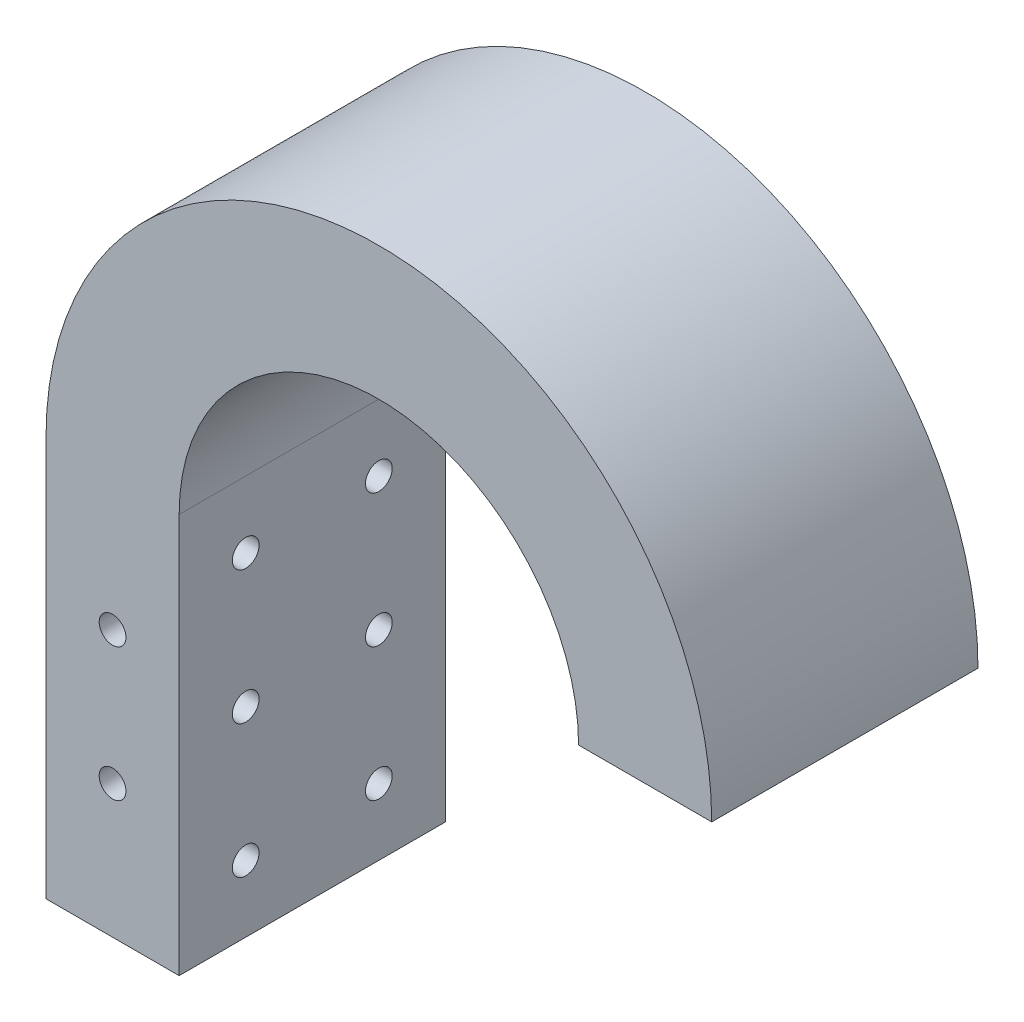
SolidWorks part; units mm, degrees
material "ABS"
ref_plane "Front" through (0, 0, 0) normal (0, 0, 1) x (1, 0, 0)
ref_plane "Top" through (0, 0, 0) normal (0, 1, 0) x (1, 0, 0)
ref_plane "Right" through (0, 0, 0) normal (1, 0, 0) x (0, 0, -1)
sketch "Sketch1" plane through (0, 0, 0) normal (0, 0, 1) x (1, 0, 0)
  line L0 (101.6, 76.2) -> (127, 76.2)
  line L1 (0, 0) -> (25.4, 0)
  line L2 (0, 0) -> (0, 76.2)
  line L4 (25.4, 0) -> (25.4, 76.2)
  arc A0 (25.4, 76.2) -> (101.6, 76.2) centre (63.5, 76.2) cw
  arc A1 (0, 76.2) -> (127, 76.2) centre (63.5, 76.2) cw
  dimension "D1" = 76.2
  dimension "D2" = 38.1
  dimension "D3" = 25.4
extrude "Boss-Extrude1" add sketch "Sketch1" along normal blind 50.8
hole_wizard "#10 Clearance Hole1" positions "Sketch2" profile "Sketch3" hole size "#10" standard "ANSI Inch"
sketch "Sketch2" plane through (0, 0, 50.8) normal (0, 0, 1) x (1, 0, 0)
  line L0 (0, 0) -> (25.4, 0) construction
  line L1 (0, 76.2) -> (0, 0) construction
  point P0 (12.7, 50.8)
  point P2 (12.7, 25.4)
  dimension "D1" = 25.4
  dimension "D2" = 25.4
  dimension "D3" = 12.7
sketch "Sketch3" plane through (12.7, 50.8, 50.8) normal (1, 0, 0) x (0, -1, 0)
  line L0 (0, 0) -> (0, 52.3328)
  line L1 (0, 52.3328) -> (2.5527, 50.799)
  line L2 (2.5527, 50.799) -> (2.5527, 0)
  line L5 (2.5527, 0) -> (0, 0)
  line L10 (0, 52.3328) -> (-2.5527, 50.799) construction
  line L11 (0, -6.35) -> (0, 107.95) construction
  dimension "Hole Dia." = 5.1054
  dimension "Hole Depth" = 50.799
  dimension "Drill Angle" = 118
hole_wizard "#10 Clearance Hole2" positions "Sketch4" profile "Sketch5" hole size "#10" standard "ANSI Inch"
sketch "Sketch4" plane through (0, 0, 0) normal (-1, 0, 0) x (0, 0, 1)
  line L0 (0, 76.2) -> (0, 0) construction
  line L1 (50.8, 0) -> (0, 0) construction
  point P0 (12.7, 38.1)
  point P2 (12.7, 12.7)
  point P4 (12.7, 63.5)
  point P12 (38.1, 63.5)
  point P14 (38.1, 12.7)
  point P16 (38.1, 38.1)
  dimension "D1" = 12.7
  dimension "D2" = 25.4
  dimension "D3" = 25.4
  dimension "D4" = 12.7
  dimension "D5" = 25.4
sketch "Sketch5" plane through (0, 38.1, 12.7) normal (0, 1, 0) x (0, 0, 1)
  line L0 (0, 0) -> (0, 26.9328)
  line L1 (0, 26.9328) -> (2.5527, 25.399)
  line L2 (2.5527, 25.399) -> (2.5527, 0)
  line L5 (2.5527, 0) -> (0, 0)
  line L10 (0, 26.9328) -> (-2.5527, 25.399) construction
  line L11 (0, -6.35) -> (0, 107.95) construction
  dimension "Hole Dia." = 5.1054
  dimension "Hole Depth" = 25.399
  dimension "Drill Angle" = 118
